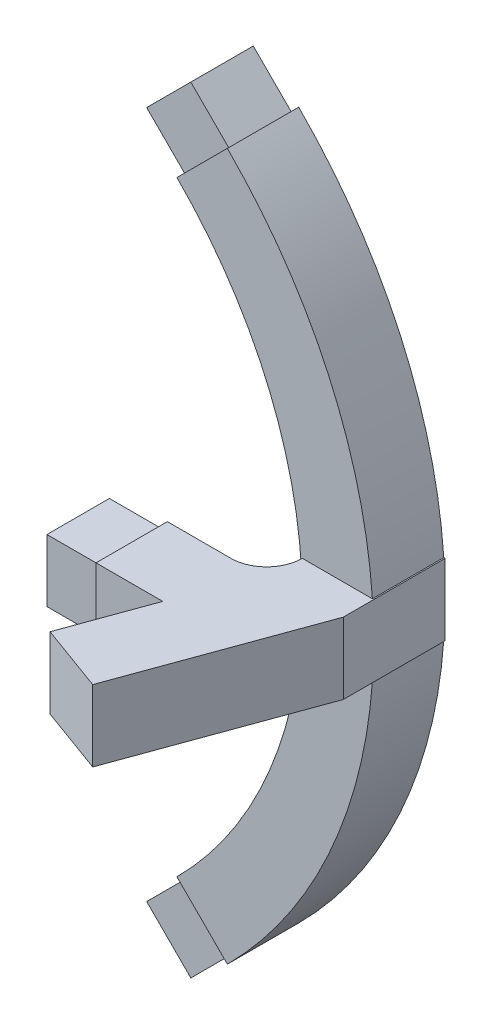
SolidWorks part; units mm, degrees
ref_plane "Front Plane" through (0, 0, 0) normal (0, 0, 1) x (1, 0, 0)
ref_plane "Top Plane" through (0, 0, 0) normal (0, 1, 0) x (1, 0, 0)
ref_plane "Right Plane" through (0, 0, 0) normal (1, 0, 0) x (0, 0, -1)
sketch "Sketch1" plane through (0, 0, 0) normal (0, 1, 0) x (1, 0, 0)
  line L0 (-27.0301, 0) -> (-50.8, 0)
  line L1 (-50.8, 0) -> (-50.8, 25.4)
  line L2 (-50.8, 25.4) -> (-17.7853, 25.4)
  line L3 (0, 0) -> (9.9259, 27.2713)
  line L4 (-1054.0602, 0) -> (-27.0301, 0) construction
  line L5 (0, 0) -> (0, -50000) construction
  line L6 (-15.4741, 31.75) -> (-15.4741, 38.1)
  line L7 (-17.7853, 25.4) -> (-15.4741, 31.75)
  line L8 (0, 0) -> (50000, 0) construction
  line L9 (0, 0) -> (-13.8673, -38.1)
  line L10 (-17.7853, 25.4) -> (-37.7355, -29.4127)
  line L11 (-15.4741, 38.1) -> (9.9259, 38.1)
  line L14 (9.9259, 31.75) -> (-15.4741, 31.75) construction
  line L16 (9.9259, 38.1) -> (9.9259, 27.2713)
  line L17 (-37.7355, -29.4127) -> (-13.8673, -38.1)
  arc A0 (-28.1741, 25.4) -> (-15.4741, 38.1) centre (-28.1741, 38.1) ccw
  point P15 (9.9259, 27.4769)
  dimension "D1" = 70
  dimension "D2" = 25.4
  dimension "D11" = 25.4
  dimension "D3" = 50.8
  dimension "D4" = 25.4
  dimension "D5" = 25.4
  dimension "D6" = 6.35
  dimension "D7" = 38.1
extrude "Boss-Extrude1" add sketch "Sketch1" along normal blind 25.4 contours L10 L2 L1 L0 | A0 L2 L7 L6
sketch "Sketch4" plane through (0, 0, -38.1) normal (0, 0, -1) x (-1, 0, 0)
  line L0 (-9.9259, 25.4) -> (-9.9259, 0) construction
  line L1 (15.4741, 25.4) -> (-9.9259, 25.4) construction
  line L2 (15.4741, 0) -> (-9.9259, 0) construction
  line L4 (-9.9259, 25.4) -> (-9.9259, 0)
  line L5 (-9.4718, 25.4) -> (-9.9259, 25.4)
  line L6 (-9.4718, 0) -> (-9.9259, 0)
  line L7 (15.4741, 25.4) -> (15.4741, 0) construction
  line L8 (15.4741, 12.7) -> (61.9515, 12.7) construction
  line L9 (60.111, -95.0631) -> (42.1505, -113.0236)
  line L10 (60.111, 120.4631) -> (42.1505, 138.4236)
  arc A0 (60.111, 120.4631) -> (60.111, -95.0631) centre (167.8741, 12.7) ccw
  arc A1 (-9.4718, 0) -> (42.1505, -113.0236) centre (167.8741, 12.7) ccw
  arc A2 (42.1505, 138.4236) -> (-9.4718, 25.4) centre (167.8741, 12.7) ccw
  point P1 (-17.447, -313.4848)
  dimension "D1" = 304.8
  dimension "D2" = 25.4
  dimension "D3" = 152.4
  dimension "D4" = 45
  dimension "D5" = 45
  dimension "D6" = 25.4
  dimension "D7" = 25.4
extrude "Boss-Extrude7" add sketch "Sketch4" along normal blind 25.4 contours A0 L9 A1 L6 L4 L5 A2 L10
sketch "Sketch5" plane through (-90.287, 90.287, 0) normal (-0.7071, 0.7071, 0) x (0, 0, 1)
  line L0 (-63.5, 68.0754) -> (-38.1, 68.0754) construction
  line L1 (-61.9125, 44.2629) -> (-39.6875, 44.2629)
  line L2 (-61.9125, 44.2629) -> (-61.9125, 66.4879)
  line L3 (-61.9125, 66.4879) -> (-39.6875, 66.4879)
  line L4 (-39.6875, 44.2629) -> (-39.6875, 66.4879)
  line L5 (-61.9125, 44.2629) -> (-39.6875, 66.4879) construction
  line L6 (-61.9125, 66.4879) -> (-39.6875, 44.2629) construction
  line L7 (-63.5, 42.6754) -> (-63.5, 68.0754) construction
  line L8 (-38.1, 42.6754) -> (-38.1, 68.0754) construction
  line L9 (-63.5, 42.6754) -> (-38.1, 42.6754) construction
  line L10 (-63.5, 68.0754) -> (-38.1, 68.0754)
  line L11 (-38.1, 42.6754) -> (-38.1, 68.0754)
  line L12 (-63.5, 42.6754) -> (-63.5, 68.0754)
  line L13 (-63.5, 42.6754) -> (-38.1, 42.6754)
  point P0 (-50.8, 55.3754)
  dimension "D1" = 1.5875
  dimension "D2" = 1.5875
  dimension "D3" = 1.5875
extrude "Boss-Extrude10" add sketch "Sketch5" along normal blind 19.05 contours L1 L4 L3 L2
sketch "Sketch6" plane through (-77.587, -77.587, 0) normal (-0.7071, -0.7071, 0) x (0, 0, 1)
  line L0 (-63.5, -24.7149) -> (-63.5, -50.1149) construction
  line L1 (-61.9125, -26.3024) -> (-39.6875, -26.3024)
  line L2 (-61.9125, -26.3024) -> (-61.9125, -48.5274)
  line L3 (-61.9125, -48.5274) -> (-39.6875, -48.5274)
  line L4 (-39.6875, -26.3024) -> (-39.6875, -48.5274)
  line L5 (-61.9125, -26.3024) -> (-39.6875, -48.5274) construction
  line L6 (-61.9125, -48.5274) -> (-39.6875, -26.3024) construction
  line L7 (-63.5, -24.7149) -> (-38.1, -24.7149) construction
  line L8 (-38.1, -24.7149) -> (-38.1, -50.1149) construction
  line L9 (-63.5, -50.1149) -> (-38.1, -50.1149) construction
  line L10 (-63.5, -24.7149) -> (-63.5, -50.1149)
  line L11 (-63.5, -24.7149) -> (-38.1, -24.7149)
  line L12 (-38.1, -24.7149) -> (-38.1, -50.1149)
  line L13 (-63.5, -50.1149) -> (-38.1, -50.1149)
  point P0 (-50.8, -37.4149)
  point P7 (-56.3624, -31.8525)
  point P10 (0, 0)
  dimension "D1" = 1.5875
  dimension "D2" = 1.5875
  dimension "D3" = 1.5875
extrude "Boss-Extrude11" add sketch "Sketch6" along normal blind 19.05 contours L4 L1 L2 L3
sketch "Sketch7" plane through (-50.8, 0, 0) normal (-1, 0, 0) x (0, 0, 1)
  line L0 (0, 25.4) -> (0, 0) construction
  line L1 (-23.8125, 1.5875) -> (-1.5875, 1.5875)
  line L2 (-23.8125, 1.5875) -> (-23.8125, 23.8125)
  line L3 (-23.8125, 23.8125) -> (-1.5875, 23.8125)
  line L4 (-1.5875, 1.5875) -> (-1.5875, 23.8125)
  line L5 (-23.8125, 1.5875) -> (-1.5875, 23.8125) construction
  line L6 (-23.8125, 23.8125) -> (-1.5875, 1.5875) construction
  line L7 (0, 25.4) -> (-25.4, 25.4) construction
  line L8 (-25.4, 25.4) -> (-25.4, 0) construction
  line L9 (-25.4, 25.4) -> (-25.4, 0) construction
  line L10 (0, 0) -> (-25.4, 0) construction
  line L11 (0, 25.4) -> (0, 0)
  line L12 (0, 25.4) -> (-25.4, 25.4)
  line L13 (-25.4, 25.4) -> (-25.4, 0)
  line L14 (0, 0) -> (-25.4, 0)
  point P0 (-12.7, 12.7)
  dimension "D1" = 1.5875
  dimension "D2" = 1.5875
  dimension "D3" = 1.5875
extrude "Boss-Extrude13" add sketch "Sketch7" along normal blind 19.05 contours L1 L4 L3 L2
